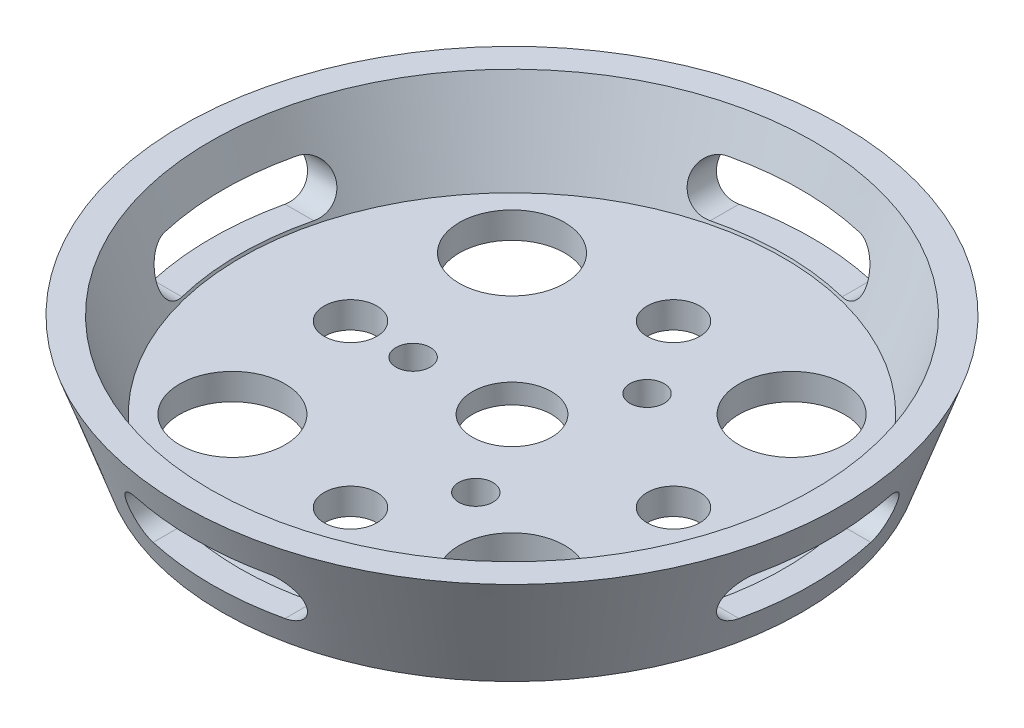
SolidWorks part; units mm, degrees
ref_plane "Front Plane" through (0, 0, 0) normal (0, 0, 1) x (1, 0, 0)
ref_plane "Top Plane" through (0, 0, 0) normal (0, 1, 0) x (1, 0, 0)
ref_plane "Right Plane" through (0, 0, 0) normal (1, 0, 0) x (0, 0, -1)
sketch "Sketch1" plane through (0, 0, 0) normal (0, 1, 0) x (1, 0, 0)
  circle A0 centre (0, 0) radius 22
  dimension "D1" = 44
ref_plane "Plane1" through (0, 8.5, 0) normal (0, 1, 0) x (1, 0, 0)
sketch "Sketch2" plane through (0, 8.5, 0) normal (0, 1, 0) x (1, 0, 0)
  circle A0 centre (0, 0) radius 25
  dimension "D1" = 50
loft "Loft1" add profiles "Sketch2", "Sketch1"
shell "Shell1" thickness 2
sketch "Sketch3" plane through (0, 0, 0) normal (0, -1, 0) x (1, 0, 0)
  line L0 (0, 0) -> (-10.6066, -10.6066) construction
  line L1 (0, 0) -> (-12.25, 0) construction
  circle A0 centre (0, 0) radius 3
  circle A1 centre (0, 0) radius 12.25 construction
  circle A2 centre (0, -12.25) radius 2
  circle A3 centre (-12.25, 0) radius 2
  circle A4 centre (0, 12.25) radius 2
  circle A5 centre (12.25, 0) radius 2
  circle A10 centre (0, 0) radius 15 construction
  circle A11 centre (-10.6066, -10.6066) radius 4
  circle A12 centre (-10.6066, 10.6066) radius 4
  circle A13 centre (10.6066, 10.6066) radius 4
  circle A14 centre (10.6066, -10.6066) radius 4
  circle A15 centre (0, 0) radius 7.5 construction
  circle A16 centre (-7.5, 0) radius 1.3
  circle A17 centre (3.75, 6.4952) radius 1.3
  circle A18 centre (3.75, -6.4952) radius 1.3
  point P15 (0, 0)
  point P24 (0, 0)
  point P26 (0, 0)
  point P33 (0, 0)
  dimension "D1" = 6
  dimension "D2" = 24.5
  dimension "D3" = 4
  dimension "D6" = 45
  dimension "D8" = 30
  dimension "D10" = 10.6066
  dimension "D7" = 8
  dimension "D12" = 15
  dimension "D13" = 2.6
  dimension "D5" = 12.25
  dimension "D11" = 15
  dimension "D15" = 7.5
  dimension "D16" = 6.4952
  dimension "D4" = 4
  dimension "D9" = 4
  dimension "D14" = 3
extrude "Cut-Extrude1" cut sketch "Sketch3" against normal through all
sketch "Sketch4" plane through (0, 0, 0) normal (0, 0, 1) x (1, 0, 0)
  line L0 (5, 4) -> (-5, 4) construction
  line L1 (5, 2.2) -> (-5, 2.2)
  line L2 (5, 5.8) -> (-5, 5.8)
  arc A0 (5, 2.2) -> (5, 5.8) centre (5, 4) ccw
  arc A1 (-5, 5.8) -> (-5, 2.2) centre (-5, 4) ccw
  point P2 (0, 4)
  dimension "D2" = 1.8
  dimension "D1" = 10
  dimension "D3" = 4
extrude "Cut-Extrude2" cut sketch "Sketch4" along normal blind 31
pattern_circular "CirPattern1" count 4 over 360 about axis through (0, 0, 0) along (0, 1, 0) of "Cut-Extrude2"
sketch "Sketch5" plane through (0, 0, 0) normal (0, -1, 0) x (1, 0, 0)
  circle A0 centre (0, 0) radius 5
  dimension "D1" = 10
extrude "Cut-Extrude3" cut sketch "Sketch5" against normal blind 0.5
